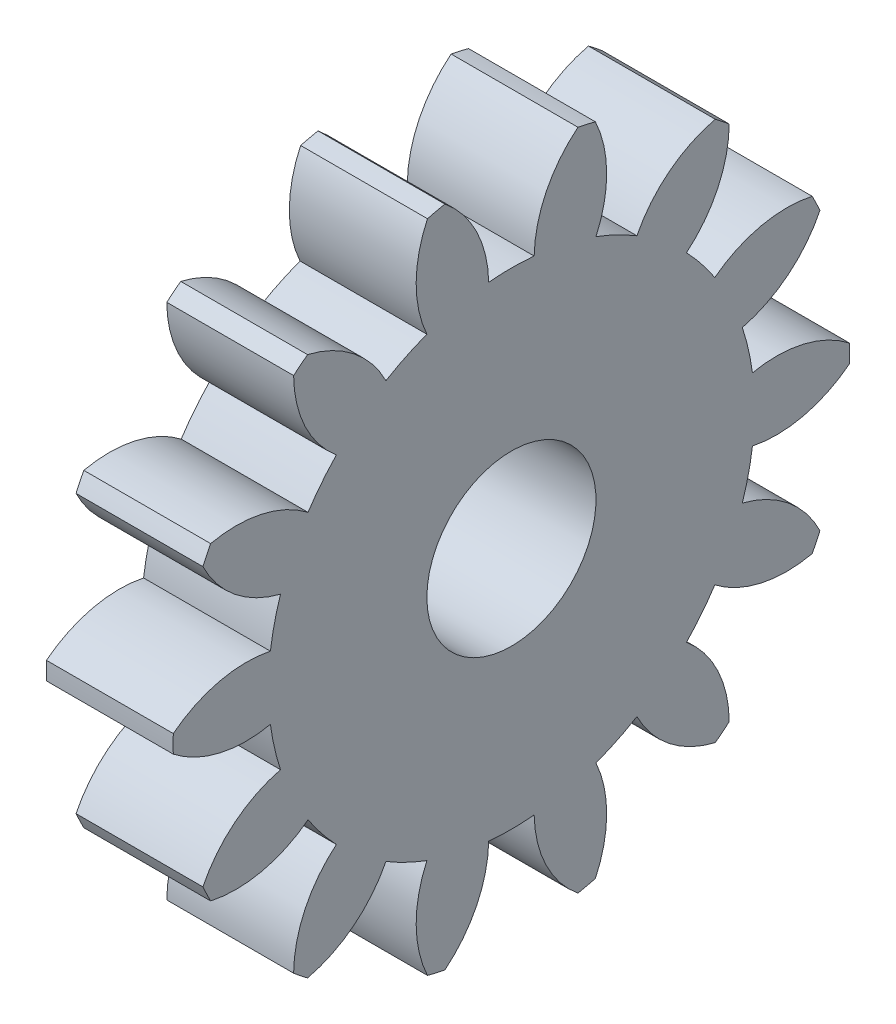
SolidWorks part; units mm, degrees
ref_plane "Plane1" through (0, 0, 0) normal (0, 0, 1) x (1, 0, 0)
ref_plane "Plane2" through (0, 0, 0) normal (0, 1, 0) x (1, 0, 0)
ref_plane "Plane3" through (0, 0, 0) normal (1, 0, 0) x (0, 0, -1)
other "Configuration Table"
sketch "HoldingSke" plane through (0, 0, 0) normal (0, 1, 0) x (1, 0, 0)
  line L0 (0, 0) -> (0.7762, -0.1935)
  line L1 (-15, 0) -> (100, 0) construction
  line L2 (0, 0) -> (-2.1039, 2.3779)
  line L3 (0, 0) -> (-11.863, 4.5341)
  line L4 (0, 0) -> (8.3795, 2.0892)
  line L5 (0, 0) -> (-46.8476, -17.4728)
  line L6 (0, 0) -> (-3.1086, -2.0974)
  line L7 (-2.1039, 2.3779) -> (8.6586, 51.2059)
  line L8 (-76.2, 54.61) -> (-75.3, 54.61)
  line L9 (-71.009, 38.7566) -> (-53.1078, 45.2721)
  line L10 (-76.2, 71.12) -> (104.1128, 71.12)
  line L11 (0, 0) -> (-3.75, 0)
  line L12 (-76.2, 101.6) -> (-76.155, 101.6)
  line L13 (24.9733, 27.94) -> (52.9518, 28.4284)
  line L14 (24.9733, 27.94) -> (24.9743, 27.94)
  line L15 (24.9733, 27.94) -> (100.4006, 29.5858)
  line L16 (-63.627, -1.25) -> (-12.827, -1.25)
  circle A0 centre (0, 0) radius 2.5
  circle A1 centre (0, 0) radius 7.1865
  circle A2 centre (0, 0) radius 37.5
  circle A3 centre (0, 0) radius 2.5
  dimension "MHD" = 14.373
  dimension "Hub_dia" = 75
  dimension "Bore" = 5
  dimension "MBD" = 5
  dimension "Num_teeth" = 14
  dimension "Pitch" = 0.8
  dimension "Overall_len" = 50
  dimension "Show_teeth" = 14
  dimension "Thickness" = 3.75
  dimension "OAL" = 50.0001
  dimension "T_dim" = 0.9
  dimension "Ap" = 20
  dimension "H" = 19.05
  dimension "Pitch_radius" = 180.3128
  dimension "Width" = 3.75
  dimension "Backlash" = 0.045
  dimension "Addendum_fac" = 1
  dimension "Dedendum_fac" = 1.25
  dimension "Clearance_fac" = 0.25
  dimension "Dedendum_add" = 0.001
  dimension "Module" = 1.25
sketch "BasProSke" plane through (0, 0, 0) normal (0, 1, 0) x (1, 0, 0)
  line L0 (-10, 0) -> (60, 0) construction
  line L1 (0, 0) -> (0, 10)
  line L2 (0, 0) -> (3.75, 0)
  line L3 (3.75, 0) -> (3.75, 10)
  line L4 (3.75, 10) -> (0, 10)
  dimension "Thickness" = 3.75
  dimension "Diameter" = 20
revolve "Base-Revolve" add sketch "BasProSke" angle 360 about L0
sketch "TooCutSke" plane through (0, 0, 0) normal (1, 0, 0) x (0, 0, -1)
  line L1 (0, 0) -> (0, 107) construction
  line L2 (0, 0) -> (-1.0584, 8.6858) construction
  line L3 (0, 0) -> (-3.8734, 16.9706) construction
  line L4 (-1.0584, 8.6858) -> (-1.9367, 8.4853) construction
  arc A0 (0.6719, 7.155) -> (-0.6719, 7.155) centre (0, 0) ccw
  arc A1 (1.993, 9.8253) -> (-1.993, 9.8253) centre (0, 0) ccw
  circle A2 centre (0, 0) radius 8.75 construction
  circle A3 centre (0, 0) radius 8.2223 construction
  arc A4 (-0.6719, 7.155) -> (-1.993, 9.8253) centre (-4.1712, 7.0857) ccw
  arc A5 (1.993, 9.8253) -> (0.6719, 7.155) centre (4.1712, 7.0857) ccw
  dimension "Root_dia" = 14.373
  dimension "Overcut_dia" = 20.0508
  dimension "Pitch_dia" = 17.5
  dimension "Base_dia" = 16.4446
  dimension "Flank_rad" = 3.5
  dimension "Half_ang" = 12.857
  dimension "Half_CT" = 0.9009
extrude "ToothCut" cut sketch "TooCutSke" along normal through all
fillet "Breaks" [suppressed] radius 0.025
fillet "RootFillets" [suppressed] radius 0.3135
pattern_circular "TeethCuts" count 14 every 25.714 about axis through (-10, 0, 0) along (1, 0, 0) of "ToothCut", "RootFillets", "Breaks"
sketch "HubNeaOneSke" plane through (0, 0, 0) normal (-1, 0, 0) x (0, 0, 1)
  circle A0 centre (0, 0) radius 7.1865
  dimension "Diameter" = 14.373
extrude "HubNearOne" [suppressed] add sketch "HubNeaOneSke" along normal blind 46.2501
sketch "HubNeaBotSke" plane through (0, 0, 0) normal (-1, 0, 0) x (0, 0, 1)
  circle A0 centre (0, 0) radius 7.1865
  dimension "Diameter" = 14.373
extrude "HubNearBoth" [suppressed] add sketch "HubNeaBotSke" along normal blind 23.125
ref_plane "FarPln" through (3.75, 0, 0) normal (1, 0, 0) x (0, 0, -1)
sketch "HubFarSke" plane through (3.75, 0, 0) normal (1, 0, 0) x (0, 0, -1)
  circle A0 centre (0, 0) radius 7.1865
  dimension "Diameter" = 14.373
extrude "HubFar" [suppressed] add sketch "HubFarSke" along normal blind 23.125
sketch "BorSke" plane through (0, 0, 0) normal (1, 0, 0) x (0, 0, -1)
  circle A0 centre (0, 0) radius 2.5
  dimension "Diameter" = 5
extrude "Bore" cut sketch "BorSke" along normal mid plane 100.0001
sketch "KeySke" plane through (0, 0, 0) normal (1, 0, 0) x (0, 0, -1)
  line L0 (-1, 0) -> (-1, 3.4)
  line L1 (-1, 3.4) -> (1, 3.4)
  line L2 (1, 3.4) -> (1, 0)
  line L3 (0, 0) -> (0, 34) construction
  line L4 (-1, 0) -> (1, 0)
  dimension "Offset" = 3.4
  dimension "Width" = 2
extrude "Keyway" [suppressed] cut sketch "KeySke" along normal mid plane 100.0001
pattern_circular "Keyway2" [suppressed] count 2 every 90 about axis through (-10, 0, 0) along (1, 0, 0)
equation "' \"Module@HoldingSke\" = 6.35"
equation "' \"Num_teeth@HoldingSke\" = 12"
equation "' \"Ap@HoldingSke\" =  20"
equation "' \"Ap@HoldingSke\" = 20"
equation "' \"Width@HoldingSke\" = 0.5 * 25.4"
equation "' \"Hub_dia@HoldingSke\"= 1 * 25.4"
equation "' \"Hub_dia@HoldingSke\" = 1 * 25.4"
equation "' \"Overall_len@HoldingSke\" = 1.0 * 25.4"
equation "' \"Bore@HoldingSke\" = 0.75 * 25.4"
equation "' \"T_dim@HoldingSke\" = 0.1 * 25.4"
equation "' \"Width@KeySke\" = 0.25 * 25.4"
equation "' \"Show_teeth@HoldingSke\" = 13"
equation "' \"Backlash@HoldingSke\" = 0.009 * 25.4"
equation "' \"Addendum_fac@HoldingSke\" = 1.0"
equation "' \"Dedendum_fac@HoldingSke\" = 1.25"
equation "' \"Dedendum_add@HoldingSke\" = 0.00005 * 25.4"
equation "' \"Clearance_fac@HoldingSke\" = 0.25"
equation "\"Pitch@HoldingSke\" = 1 / \"Module@HoldingSke\""
equation "\"Overcut_dia@TooCutSke\" = (\"Num_teeth@HoldingSke\" + 2 * \"Addendum_fac@HoldingSke\") / \"Pitch@HoldingSke\" + 0.002 * 25.4"
equation "\"Pitch_dia@TooCutSke\" = \"Num_teeth@HoldingSke\" / \"Pitch@HoldingSke\""
equation "\"Base_dia@TooCutSke\" = \"Num_teeth@HoldingSke\" / \"Pitch@HoldingSke\" * cos((\"Ap@HoldingSke\"  * 3.14159265 / 180))"
equation "\"Root_dia@TooCutSke\" = (\"Num_teeth@HoldingSke\" + 2) / \"Pitch@HoldingSke\" - 2 * (\"Addendum_fac@HoldingSke\" + \"Dedendum_fac@HoldingSke\") / \"Pitch@HoldingSke\" - \"Dedendum_add@HoldingSke\" * 2"
equation "\"Half_ang@TooCutSke\" = 180 / \"Num_teeth@HoldingSke\""
equation "\"Half_CT@TooCutSke\" = \"Num_teeth@HoldingSke\" / \"Pitch@HoldingSke\" * sin((3.14159265 / 2 / \"Num_teeth@HoldingSke\")) / 2 - 7 * \"Backlash@HoldingSke\" / 4"
equation "\"Flank_rad@TooCutSke\" = \"Num_teeth@HoldingSke\" / \"Pitch@HoldingSke\" / 5"
equation "\"Radius@RootFillets\" = \"Clearance_fac@HoldingSke\" / \"Pitch@HoldingSke\" + \"Dedendum_add@HoldingSke\""
equation "\"Break_rad@Breaks\" = 0.02 / \"Pitch@HoldingSke\""
equation "\"Thickness@HoldingSke\" = \"Width@HoldingSke\""
equation "\"OAL@HoldingSke\" = \"Thickness@HoldingSke\""
equation "\"MHD@HoldingSke\" = (\"Num_teeth@HoldingSke\" + 2) / \"Pitch@HoldingSke\" - 2 * (\"Addendum_fac@HoldingSke\" + \"Dedendum_fac@HoldingSke\")  / \"Pitch@HoldingSke\" - \"Dedendum_add@HoldingSke\" * 2"
equation "\"MBD@HoldingSke\" = (\"Num_teeth@HoldingSke\" + 2) / \"Pitch@HoldingSke\" - 2 * (\"Addendum_fac@HoldingSke\" + \"Dedendum_fac@HoldingSke\")  / \"Pitch@HoldingSke\" - \"Dedendum_add@HoldingSke\" * 2 - 0.002 * 25.4"
equation "\"MHD@HoldingSke\" = ((sgn( \"MHD@HoldingSke\" - \"Hub_dia@HoldingSke\" )-1)*( \"MHD@HoldingSke\" - \"Hub_dia@HoldingSke\" ))/-2+ \"Hub_dia@HoldingSke\""
equation "\"MBD@HoldingSke\" = ((sgn( \"MBD@HoldingSke\" - \"Bore@HoldingSke\" )-1)*( \"MBD@HoldingSke\" - \"Bore@HoldingSke\" ))/-2+ \"Bore@HoldingSke\""
equation "\"OAL@HoldingSke\" = ((sgn( \"OAL@HoldingSke\" - \"Overall_len@HoldingSke\" )+1)*( \"OAL@HoldingSke\" - \"Overall_len@HoldingSke\" ))/2 + \"Overall_len@HoldingSke\" + 0.000002 * 25.4"
equation "\"Num_teeth@TeethCuts\" = int( \"Show_teeth@HoldingSke\" ) + 1"
equation "\"Num_teeth@TeethCuts\" = ((sgn( \"Num_teeth@TeethCuts\" - \"Num_teeth@HoldingSke\" )-1)*( \"Num_teeth@TeethCuts\" - \"Num_teeth@HoldingSke\" ))/-2+ \"Num_teeth@HoldingSke\""
equation "\"Num_teeth@TeethCuts\" = ((sgn( \"Num_teeth@TeethCuts\" - 2.0)+1)*( \"Num_teeth@TeethCuts\" - 2.0))/2 +2.0"
equation "\"Angle@TeethCuts\" = 360.0 / \"Num_teeth@HoldingSke\""
equation "\"Diameter@BasProSke\" = (\"Num_teeth@HoldingSke\" + 2 * \"Addendum_fac@HoldingSke\") / \"Pitch@HoldingSke\""
equation "\"Thickness@BasProSke\"  = \"Thickness@HoldingSke\""
equation "' \"Fillet_rad@BasProSke\" =  \"Thickness@HoldingSke\" * 0.05"
equation "' \"Fillet_rad@BasProSke\" = \"Thickness@HoldingSke\" * 0.05"
equation "\"MHD@HoldingSke\" = ((sgn( \"MHD@HoldingSke\" - \"Root_dia@TooCutSke\" )-1)*( \"MHD@HoldingSke\" - \"Root_dia@TooCutSke\" ))/-2+ \"Root_dia@TooCutSke\""
equation "\"Diameter@HubNeaOneSke\" = \"MHD@HoldingSke\""
equation "\"Length@HubNearOne\" = \"OAL@HoldingSke\" - \"Thickness@BasProSke\""
equation "\"Diameter@HubNeaBotSke\" = \"MHD@HoldingSke\""
equation "\"Length@HubNearBoth\" = ( \"OAL@HoldingSke\" - \"Thickness@BasProSke\" ) / 2.0"
equation "\"Thickness@FarPln\" = \"Thickness@BasProSke\""
equation "\"Diameter@HubFarSke\" = \"MHD@HoldingSke\""
equation "\"Length@HubFar\" = ( \"OAL@HoldingSke\" - \"Thickness@BasProSke\" ) / 2.0"
equation "\"Diameter@BorSke\" = \"MBD@HoldingSke\""
equation "\"D1@Bore\" = \"OAL@HoldingSke\" * 2.0"
equation "\"D1@Keyway\" = \"OAL@HoldingSke\" * 2.0"
equation "\"Offset@KeySke\" = \"T_dim@HoldingSke\" + \"MBD@HoldingSke\" / 2.0"
